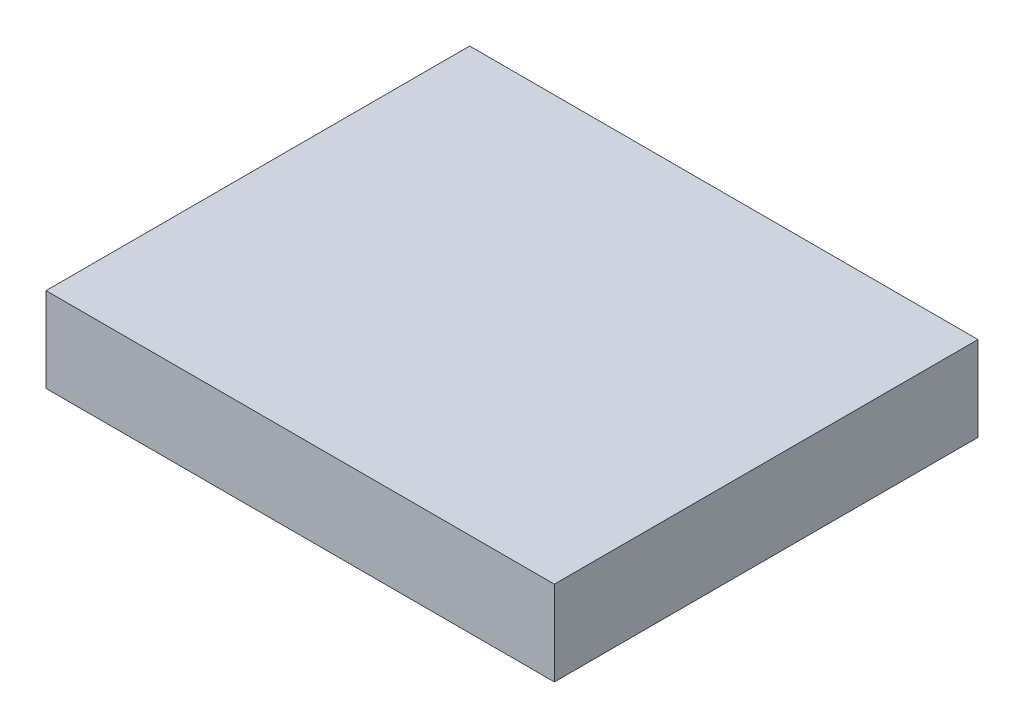
SolidWorks part; units mm, degrees
material "Balsa"
ref_plane "Front Plane" through (0, 0, 0) normal (0, 0, 1) x (1, 0, 0)
ref_plane "Top Plane" through (0, 0, 0) normal (0, 1, 0) x (1, 0, 0)
ref_plane "Right Plane" through (0, 0, 0) normal (1, 0, 0) x (0, 0, -1)
sketch "Sketch1" plane through (0, 0, 0) normal (0, 1, 0) x (1, 0, 0)
  line L1 (0, 0) -> (30, 0)
  line L2 (0, 0) -> (0, 25)
  line L3 (0, 25) -> (30, 25)
  line L4 (30, 0) -> (30, 25)
  dimension "D1" = 25
  dimension "D2" = 30
extrude "Boss-Extrude1" add sketch "Sketch1" along normal blind 5
